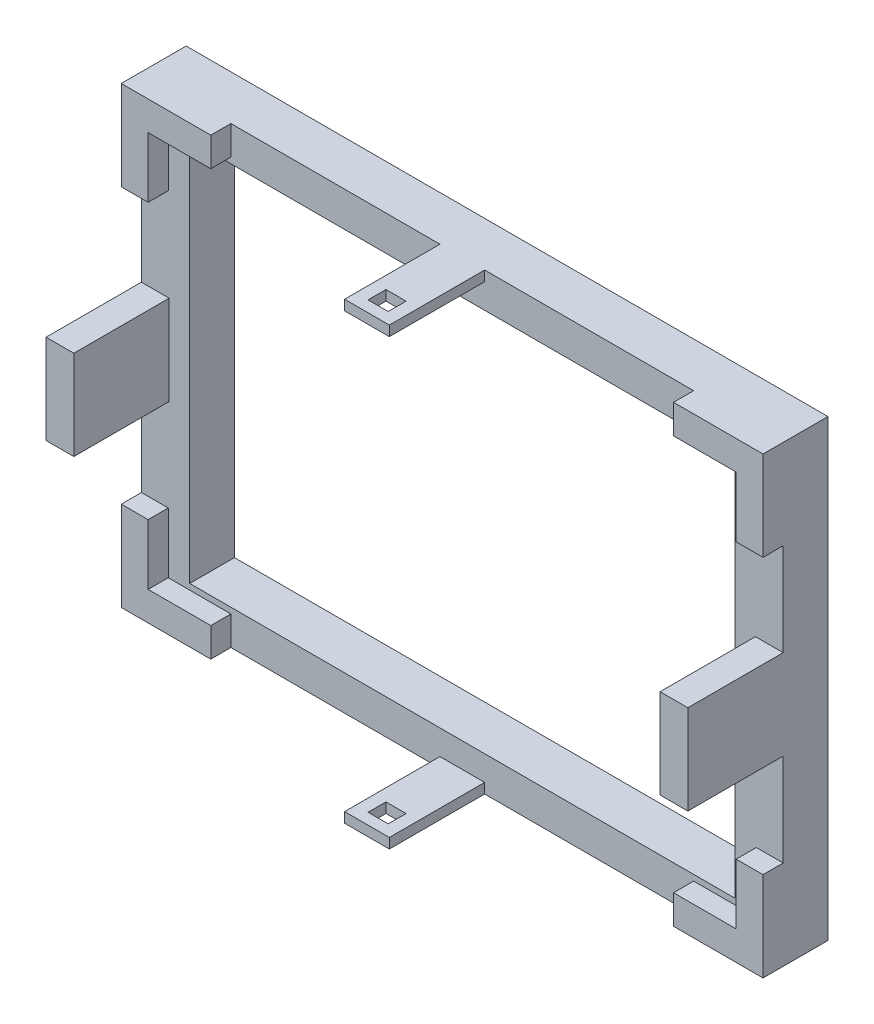
SolidWorks part; units mm, degrees
ref_plane "Front Plane" through (0, 0, 0) normal (0, 0, 1) x (1, 0, 0)
ref_plane "Top Plane" through (0, 0, 0) normal (0, 1, 0) x (1, 0, 0)
ref_plane "Right Plane" through (0, 0, 0) normal (1, 0, 0) x (0, 0, -1)
sketch "Sketch2" plane through (0, 0, 0) normal (0, 0, 1) x (1, 0, 0)
  line L7 (-71.7, -50.7) -> (71.7, -50.7)
  line L8 (-71.7, -50.7) -> (-71.7, 50.7)
  line L9 (-71.7, 50.7) -> (71.7, 50.7)
  line L10 (71.7, -50.7) -> (71.7, 50.7)
  line L11 (-71.7, -50.7) -> (71.7, 50.7) construction
  line L12 (-71.7, 50.7) -> (71.7, -50.7) construction
  point P12 (0, 0)
  dimension "D1" = 143.4
  dimension "D2" = 101.4
extrude "Boss-Extrude2" add sketch "Sketch2" along normal blind 10
sketch "Sketch3" plane through (0, 0, 10) normal (0, 0, 1) x (1, 0, 0)
  line L0 (0, 50.7) -> (0, -50.7) construction
  line L1 (71.7, 50.7) -> (-71.7, 50.7) construction
  line L2 (-71.7, -50.7) -> (71.7, -50.7) construction
  line L3 (-71.7, 0) -> (71.7, 0) construction
  line L4 (-71.7, 50.7) -> (-71.7, -50.7) construction
  line L5 (71.7, -50.7) -> (71.7, 50.7) construction
  line L7 (60.9, 42.9) -> (-60.9, 42.9)
  line L8 (60.9, 42.9) -> (60.9, -42.9)
  line L9 (60.9, -42.9) -> (-60.9, -42.9)
  line L10 (-60.9, 42.9) -> (-60.9, -42.9)
  line L11 (60.9, 42.9) -> (-60.9, -42.9) construction
  line L12 (60.9, -42.9) -> (-60.9, 42.9) construction
  point P12 (0, 0)
  dimension "D1" = 7.8
  dimension "D2" = 10.8
extrude "Cut-Extrude1" cut sketch "Sketch3" against normal through all
sketch "Sketch4" plane through (0, 0, 0) normal (0, 0, -1) x (-1, 0, 0)
  line L0 (-71.7, -50.7) -> (-71.7, 50.7) construction
  line L1 (71.7, -50.7) -> (-71.7, -50.7)
  line L2 (71.7, -50.7) -> (71.7, -165.8248)
  line L3 (71.7, -165.8248) -> (-71.7, -165.8248)
  line L4 (-71.7, -50.7) -> (-71.7, -165.8248)
  line L5 (71.7, 50.7) -> (71.7, -50.7) construction
  line L6 (140.9464, -165.8248) -> (13.3464, -165.8248) construction
  line L7 (-71.7, 50.7) -> (71.7, 50.7)
  line L8 (-71.7, 50.7) -> (-71.7, -80.3248)
  line L10 (71.7, 50.7) -> (71.7, -80.3248)
  line L11 (71.7, -80.3248) -> (142.0369, -80.3248)
  line L12 (71.7, -80.3248) -> (71.7, -113.0908)
  line L13 (71.7, -113.0908) -> (142.0369, -113.0908)
  line L14 (142.0369, -80.3248) -> (142.0369, -113.0908)
extrude "Boss-Extrude3" [suppressed] add sketch "Sketch4" along normal blind 23
sketch "Sketch6" plane through (0, 0, 10) normal (0, 0, 1) x (1, 0, 0)
  line L0 (51.7, 50.7) -> (51.7, 44.2)
  line L1 (51.7, 44.2) -> (65.7, 44.2)
  line L2 (71.7, 30.7) -> (65.7, 30.7)
  line L5 (71.7, -50.7) -> (71.7, 50.7) construction
  line L6 (65.7, 30.7) -> (65.7, 44.2)
  line L8 (71.7, 50.7) -> (-71.7, 50.7) construction
  line L9 (71.7, 30.7) -> (71.7, 50.7)
  line L11 (71.7, 50.7) -> (51.7, 50.7)
  dimension "D2" = 6.5
  dimension "D3" = 6
  dimension "D1" = 20
extrude "Boss-Extrude4" add sketch "Sketch6" along normal blind 4.5
sketch "Sketch8" plane through (0, 0, 10) normal (0, 0, 1) x (1, 0, 0)
  line L1 (71.7, -50.7) -> (71.7, 30.7) construction
  line L3 (71.7, -10) -> (65.5, -10)
  line L4 (71.7, -10) -> (71.7, 10)
  line L5 (71.7, 10) -> (65.5, 10)
  line L6 (65.5, -10) -> (65.5, 10)
  line L7 (0, 0) -> (71.7, 0) construction
  line L8 (0, 0) -> (0, 50.7) construction
  line L9 (51.7, 50.7) -> (-71.7, 50.7) construction
  line L10 (71.7, -10) -> (65.5, 10) construction
  line L11 (-5, 50.7) -> (5, 50.7)
  line L12 (-5, 50.7) -> (-5, 48.45)
  line L13 (-5, 48.45) -> (5, 48.45)
  line L14 (5, 50.7) -> (5, 48.45)
  line L15 (-5, 50.7) -> (5, 48.45) construction
  line L16 (-5, 48.45) -> (5, 50.7) construction
  line L17 (71.7, 10) -> (65.5, -10) construction
  point P0 (68.6, 0)
  point P10 (0, 49.575)
  dimension "D2" = 6.2
  dimension "D3" = 2.25
  dimension "D4" = 10
  dimension "D5" = 20
extrude "Boss-Extrude5" add sketch "Sketch8" along normal blind 21.3
sketch "Sketch10" plane through (0, 50.7, 0) normal (0, 1, 0) x (1, 0, 0)
  line L0 (5, -31.3) -> (-5, -31.3) construction
  line L1 (2.25, -28.8) -> (-2.25, -28.8)
  line L2 (2.25, -28.8) -> (2.25, -24.8)
  line L3 (2.25, -24.8) -> (-2.25, -24.8)
  line L4 (-2.25, -28.8) -> (-2.25, -24.8)
  line L5 (2.25, -28.8) -> (-2.25, -24.8) construction
  line L6 (2.25, -24.8) -> (-2.25, -28.8) construction
  line L7 (0, -31.3) -> (0, 0) construction
  line L8 (71.7, 0) -> (-71.7, 0) construction
  point P0 (0, -26.8)
  dimension "D1" = 2.5
  dimension "D2" = 4
  dimension "D3" = 4.5
extrude "Cut-Extrude3" cut sketch "Sketch10" against normal up to next contours L2 L3 L4 L1
sketch "Sketch7" [suppressed] plane through (71.7, 0, 0) normal (1, 0, 0) x (0, 0, -1)
  line L0 (-32.3, 0) -> (-19.7787, 0) construction
  line L2 (-32.3, -5) -> (-32.3, 5) construction
  line L3 (-25.8, 2.25) -> (-29.8, 2.25)
  line L4 (-25.8, 2.25) -> (-25.8, -2.25)
  line L5 (-25.8, -2.25) -> (-29.8, -2.25)
  line L6 (-29.8, 2.25) -> (-29.8, -2.25)
  line L7 (-25.8, 2.25) -> (-29.8, -2.25) construction
  line L8 (-25.8, -2.25) -> (-29.8, 2.25) construction
  point P5 (-27.8, 0)
  dimension "D1" = 2.5
  dimension "D2" = 4
  dimension "D3" = 4.5
extrude "Cut-Extrude2" [suppressed] cut sketch "Sketch7" against normal up to next
mirror "Mirror1" about plane through (0, 0, 0) normal (0, 1, 0) of "Cut-Extrude2", "Cut-Extrude3", "Boss-Extrude5", "Boss-Extrude4"
mirror "Mirror2" about plane through (0, 0, 0) normal (1, 0, 0) of "Cut-Extrude2", "Mirror1", "Boss-Extrude5"
fillet "Fillet2" [suppressed] radius 1
fillet "Fillet3" [suppressed] radius 0.5
fillet "Fillet4" [suppressed] radius 0.5
